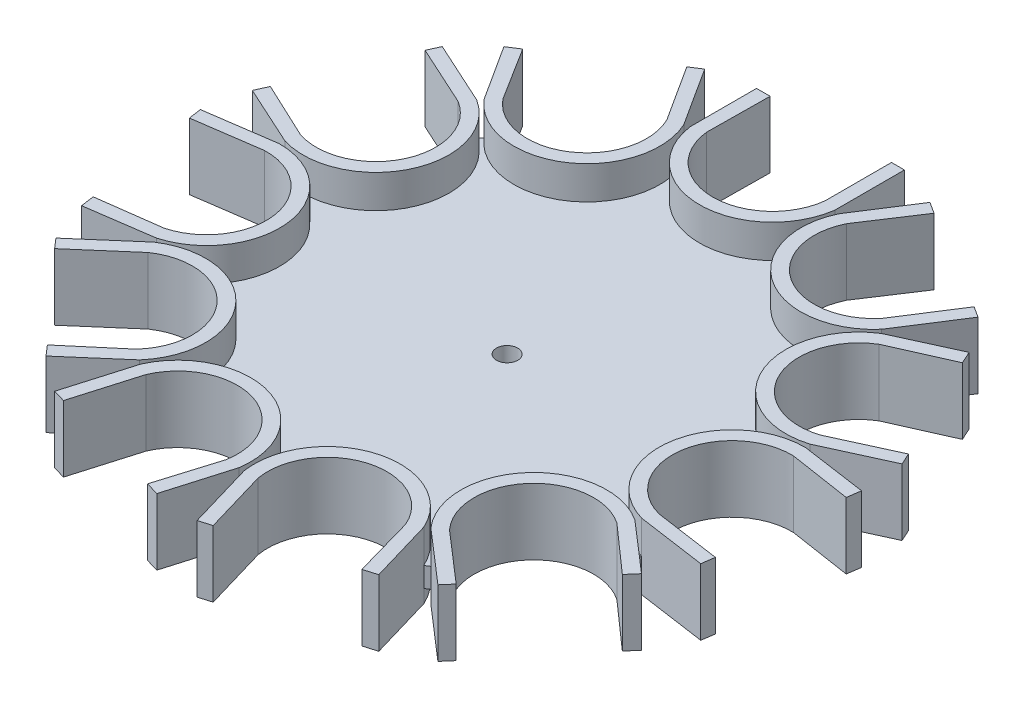
SolidWorks part; units mm, degrees
ref_plane "Front Plane" through (0, 0, 0) normal (0, 0, 1) x (1, 0, 0)
ref_plane "Top Plane" through (0, 0, 0) normal (0, 1, 0) x (1, 0, 0)
ref_plane "Right Plane" through (0, 0, 0) normal (1, 0, 0) x (0, 0, -1)
sketch "Sketch2" plane through (0, 0, 0) normal (0, 1, 0) x (1, 0, 0)
  line L0 (0, 0) -> (0, 40)
  line L1 (-9, 40) -> (-9, 45)
  line L2 (-9, 45) -> (9, 45)
  line L3 (9, 45) -> (9, 40)
  line L4 (14.0544, 38.5159) -> (16.7576, 42.7222)
  line L5 (31.9001, 32.9906) -> (29.1969, 28.7844)
  line L6 (16.7576, 42.7222) -> (31.9001, 32.9906)
  line L7 (32.6465, 24.8033) -> (37.1947, 26.8804)
  line L8 (44.6722, 10.507) -> (40.124, 8.4299)
  line L9 (37.1947, 26.8804) -> (44.6722, 10.507)
  line L10 (40.8737, 3.2158) -> (45.8228, 2.5042)
  line L11 (43.2611, -15.3126) -> (38.312, -14.601)
  line L12 (45.8228, 2.5042) -> (43.2611, -15.3126)
  line L13 (36.1237, -19.3927) -> (39.9025, -22.667)
  line L14 (28.115, -36.2705) -> (24.3362, -32.9962)
  line L15 (39.9025, -22.667) -> (28.115, -36.2705)
  line L16 (19.9047, -35.8441) -> (21.3134, -40.6416)
  line L17 (4.0425, -45.7128) -> (2.6339, -40.9153)
  line L18 (21.3134, -40.6416) -> (4.0425, -45.7128)
  line L19 (-2.6339, -40.9153) -> (-4.0425, -45.7128)
  line L20 (-21.3134, -40.6416) -> (-19.9047, -35.8441)
  line L21 (-4.0425, -45.7128) -> (-21.3134, -40.6416)
  line L22 (-24.3362, -32.9962) -> (-28.115, -36.2705)
  line L23 (-39.9025, -22.667) -> (-36.1237, -19.3927)
  line L24 (-28.115, -36.2705) -> (-39.9025, -22.667)
  line L25 (-38.312, -14.601) -> (-43.2611, -15.3126)
  line L26 (-45.8228, 2.5042) -> (-40.8737, 3.2158)
  line L27 (-43.2611, -15.3126) -> (-45.8228, 2.5042)
  line L28 (-40.124, 8.4299) -> (-44.6722, 10.507)
  line L29 (-37.1947, 26.8804) -> (-32.6465, 24.8033)
  line L30 (-44.6722, 10.507) -> (-37.1947, 26.8804)
  line L31 (-29.1969, 28.7844) -> (-31.9001, 32.9906)
  line L32 (-16.7576, 42.7222) -> (-14.0544, 38.5159)
  line L33 (-31.9001, 32.9906) -> (-16.7576, 42.7222)
  arc A0 (-9, 40) -> (9, 40) centre (0, 40) ccw
  arc A1 (14.0544, 38.5159) -> (29.1969, 28.7844) centre (21.6256, 33.6501) ccw
  arc A2 (32.6465, 24.8033) -> (40.124, 8.4299) centre (36.3853, 16.6166) ccw
  arc A3 (40.8737, 3.2158) -> (38.312, -14.601) centre (39.5929, -5.6926) ccw
  arc A4 (36.1237, -19.3927) -> (24.3362, -32.9962) centre (30.23, -26.1944) ccw
  arc A5 (19.9047, -35.8441) -> (2.6339, -40.9153) centre (11.2693, -38.3797) ccw
  arc A6 (-2.6339, -40.9153) -> (-19.9047, -35.8441) centre (-11.2693, -38.3797) ccw
  arc A7 (-24.3362, -32.9962) -> (-36.1237, -19.3927) centre (-30.23, -26.1944) ccw
  arc A8 (-38.312, -14.601) -> (-40.8737, 3.2158) centre (-39.5929, -5.6926) ccw
  arc A9 (-40.124, 8.4299) -> (-32.6465, 24.8033) centre (-36.3853, 16.6166) ccw
  arc A10 (-29.1969, 28.7844) -> (-14.0544, 38.5159) centre (-21.6256, 33.6501) ccw
  circle A11 centre (0, 0) radius 45.8912
  point P60 (0, 0)
  dimension "D2" = 18
  dimension "D1" = 40
  dimension "D3" = 5
  dimension "D4" = 11
extrude "Boss-Extrude4" add sketch "Sketch2" along normal blind 3
sketch "Sketch4" plane through (0, 3, 0) normal (0, 1, 0) x (1, 0, 0)
  circle A0 centre (0, 0) radius 1.6
  dimension "D1" = 3.2
extrude "Cut-Extrude1" cut sketch "Sketch4" against normal blind 3
fillet "Fillet1" [suppressed] radius 5
sketch "Sketch5" plane through (0, 3, 0) normal (0, 1, 0) x (1, 0, 0)
  arc A0 (-30.6093, 34.1917) -> (-18.3862, 42.0469) centre (-21.6256, 33.6501) ccw
  arc A1 (-7.2648, 45.3125) -> (7.2648, 45.3125) centre (0, 40) ccw
  arc A2 (18.3862, 42.0469) -> (30.6093, 34.1917) centre (21.6256, 33.6501) ccw
  arc A3 (38.1998, 25.4318) -> (44.2356, 12.2152) centre (36.3853, 16.6166) ccw
  arc A4 (45.8852, 0.7422) -> (43.8174, -13.6395) centre (39.5929, -5.6926) ccw
  arc A5 (39.0023, -24.183) -> (29.4875, -35.1637) centre (30.23, -26.1944) ccw
  arc A6 (19.7365, -41.4303) -> (5.7955, -45.5238) centre (11.2693, -38.3797) ccw
  arc A7 (-5.7955, -45.5238) -> (-19.7365, -41.4303) centre (-11.2693, -38.3797) ccw
  arc A8 (-29.4875, -35.1637) -> (-39.0023, -24.183) centre (-30.23, -26.1944) ccw
  arc A9 (-43.8174, -13.6395) -> (-45.8852, 0.7422) centre (-39.5929, -5.6926) ccw
  arc A10 (-44.2356, 12.2152) -> (-38.1998, 25.4318) centre (-36.3853, 16.6166) ccw
  arc A11 (-44.5811, 10.887) -> (-37.4222, 26.5627) centre (-36.3853, 16.6166) ccw
  arc A12 (-31.6181, 33.2611) -> (-17.1207, 42.5779) centre (-21.6256, 33.6501) ccw
  arc A13 (-8.6165, 45.075) -> (8.6165, 45.075) centre (0, 40) ccw
  arc A14 (17.1207, 42.5779) -> (31.6181, 33.2611) centre (21.6256, 33.6501) ccw
  arc A15 (37.4222, 26.5627) -> (44.5811, 10.887) centre (36.3853, 16.6166) ccw
  arc A16 (45.8425, 2.114) -> (43.3899, -14.9437) centre (39.5929, -5.6926) ccw
  arc A17 (39.708, -23.0059) -> (28.4228, -36.0298) centre (30.23, -26.1944) ccw
  arc A18 (20.9666, -40.8216) -> (4.4316, -45.6767) centre (11.2693, -38.3797) ccw
  arc A19 (-4.4316, -45.6767) -> (-20.9666, -40.8216) centre (-11.2693, -38.3797) ccw
  arc A20 (-28.4228, -36.0298) -> (-39.708, -23.0059) centre (-30.23, -26.1944) ccw
  arc A21 (-43.3899, -14.9437) -> (-45.8425, 2.114) centre (-39.5929, -5.6926) ccw
  arc A22 (-44.2356, 12.2152) -> (-44.5811, 10.887) centre (0, 0) ccw
  arc A23 (-30.6093, 34.1917) -> (-31.6181, 33.2611) centre (0, 0) ccw
  arc A24 (-7.2648, 45.3125) -> (-8.6165, 45.075) centre (0, 0) ccw
  arc A25 (18.3862, 42.0469) -> (17.1207, 42.5779) centre (0, 0) ccw
  arc A26 (38.1998, 25.4318) -> (37.4222, 26.5627) centre (0, 0) ccw
  arc A27 (45.8852, 0.7422) -> (45.8425, 2.114) centre (0, 0) ccw
  arc A28 (39.0023, -24.183) -> (39.708, -23.0059) centre (0, 0) ccw
  arc A29 (-20.9666, -40.8216) -> (-19.7365, -41.4303) centre (0, 0) ccw
  arc A30 (-29.4875, -35.1637) -> (-28.4228, -36.0298) centre (0, 0) ccw
  arc A31 (-43.8174, -13.6395) -> (-43.3899, -14.9437) centre (0, 0) ccw
  circle A32 centre (-21.6256, 33.6501) radius 10 construction
  circle A33 centre (-21.6256, 33.6501) radius 9 construction
  circle A34 centre (0, 40) radius 10 construction
  circle A35 centre (0, 40) radius 9 construction
  circle A36 centre (21.6256, 33.6501) radius 10 construction
  circle A37 centre (21.6256, 33.6501) radius 9 construction
  circle A38 centre (36.3853, 16.6166) radius 10 construction
  circle A39 centre (36.3853, 16.6166) radius 9 construction
  circle A40 centre (39.5929, -5.6926) radius 10 construction
  circle A41 centre (39.5929, -5.6926) radius 9 construction
  circle A42 centre (-39.5929, -5.6926) radius 10 construction
  circle A43 centre (-39.5929, -5.6926) radius 9 construction
  circle A44 centre (-36.3853, 16.6166) radius 10 construction
  circle A45 centre (-36.3853, 16.6166) radius 9 construction
  circle A46 centre (-30.23, -26.1944) radius 10 construction
  circle A47 centre (-30.23, -26.1944) radius 9 construction
  arc A48 (-5.7955, -45.5238) -> (-4.4316, -45.6767) centre (0, 0) ccw
  circle A49 centre (-11.2693, -38.3797) radius 10 construction
  circle A50 centre (-11.2693, -38.3797) radius 9 construction
  arc A51 (19.7365, -41.4303) -> (20.9666, -40.8216) centre (0, 0) ccw
  circle A52 centre (11.2693, -38.3797) radius 9 construction
  circle A53 centre (11.2693, -38.3797) radius 10 construction
  circle A54 centre (30.23, -26.1944) radius 10 construction
  circle A55 centre (30.23, -26.1944) radius 9 construction
  arc A56 (-17.1207, 42.5779) -> (-18.3862, 42.0469) centre (0, 0) ccw
  arc A57 (8.6165, 45.075) -> (7.2648, 45.3125) centre (0, 0) ccw
  arc A58 (31.6181, 33.2611) -> (30.6093, 34.1917) centre (0, 0) ccw
  arc A59 (44.5811, 10.887) -> (44.2356, 12.2152) centre (0, 0) ccw
  arc A60 (43.3899, -14.9437) -> (43.8174, -13.6395) centre (0, 0) ccw
  arc A61 (28.4228, -36.0298) -> (29.4875, -35.1637) centre (0, 0) ccw
  arc A62 (4.4316, -45.6767) -> (5.7955, -45.5238) centre (0, 0) ccw
  arc A63 (-39.708, -23.0059) -> (-39.0023, -24.183) centre (0, 0) ccw
  arc A64 (-45.8425, 2.114) -> (-45.8852, 0.7422) centre (0, 0) ccw
  arc A65 (-37.4222, 26.5627) -> (-38.1998, 25.4318) centre (0, 0) ccw
  point P26 (0, 0)
  dimension "D2" = 1
  dimension "D3" = 1
  dimension "D1" = 11
extrude "Boss-Extrude5" [suppressed] add sketch "Sketch5" along normal blind 5
fillet "Fillet2" [suppressed] radius 5
sketch "Sketch8" plane through (0, 3, 0) normal (0, 1, 0) x (1, 0, 0)
  arc A0 (-8.9429, 38.9875) -> (8.9429, 38.9875) centre (0, 40) ccw
  arc A1 (-10.8955, 38.4875) -> (10.8955, 38.4875) centre (0, 40) ccw
  arc A2 (10.8955, 38.4875) -> (8.9429, 38.9875) centre (0, 0) ccw
  arc A3 (-8.9429, 38.9875) -> (-10.8955, 38.4875) centre (0, 0) ccw
  circle A4 centre (0, 40) radius 11 construction
  circle A5 centre (0, 40) radius 9 construction
  arc A6 (11.642, 38.2683) -> (29.9738, 26.4872) centre (21.6256, 33.6501) ccw
  arc A7 (29.9738, 26.4872) -> (28.6015, 27.9635) centre (0, 0) ccw
  arc A8 (13.555, 37.6333) -> (28.6015, 27.9635) centre (21.6256, 33.6501) ccw
  arc A9 (13.555, 37.6333) -> (11.642, 38.2683) centre (0, 0) ccw
  arc A10 (30.4833, 25.8992) -> (39.5356, 6.0774) centre (36.3853, 16.6166) ccw
  arc A11 (39.5356, 6.0774) -> (39.1793, 8.0613) centre (0, 0) ccw
  arc A12 (31.7493, 24.3307) -> (39.1793, 8.0613) centre (36.3853, 16.6166) ccw
  arc A13 (31.7493, 24.3307) -> (30.4833, 25.8992) centre (0, 0) ccw
  arc A14 (39.6463, 5.3073) -> (36.5452, -16.262) centre (39.5929, -5.6926) ccw
  arc A15 (36.5452, -16.262) -> (37.318, -14.4003) centre (0, 0) ccw
  arc A16 (39.8634, 3.3033) -> (37.318, -14.4003) centre (39.5929, -5.6926) ccw
  arc A17 (39.8634, 3.3033) -> (39.6463, 5.3073) centre (0, 0) ccw
  arc A18 (36.222, -16.9697) -> (21.9519, -33.4382) centre (30.23, -26.1944) ccw
  arc A19 (21.9519, -33.4382) -> (23.6085, -32.2899) centre (0, 0) ccw
  arc A20 (35.3211, -18.7728) -> (23.6085, -32.2899) centre (30.23, -26.1944) ccw
  arc A21 (35.3211, -18.7728) -> (36.222, -16.9697) centre (0, 0) ccw
  arc A22 (21.2974, -33.8589) -> (0.389, -39.9981) centre (11.2693, -38.3797) ccw
  arc A23 (0.389, -39.9981) -> (2.4034, -39.9277) centre (0, 0) ccw
  arc A24 (19.5647, -34.8887) -> (2.4034, -39.9277) centre (11.2693, -38.3797) ccw
  arc A25 (19.5647, -34.8887) -> (21.2974, -33.8589) centre (0, 0) ccw
  arc A26 (-0.389, -39.9981) -> (-21.2974, -33.8589) centre (-11.2693, -38.3797) ccw
  arc A27 (-21.2974, -33.8589) -> (-19.5647, -34.8887) centre (0, 0) ccw
  arc A28 (-2.4034, -39.9277) -> (-19.5647, -34.8887) centre (-11.2693, -38.3797) ccw
  arc A29 (-2.4034, -39.9277) -> (-0.389, -39.9981) centre (0, 0) ccw
  arc A30 (-21.9519, -33.4382) -> (-36.222, -16.9697) centre (-30.23, -26.1944) ccw
  arc A31 (-36.222, -16.9697) -> (-35.3211, -18.7728) centre (0, 0) ccw
  arc A32 (-23.6085, -32.2899) -> (-35.3211, -18.7728) centre (-30.23, -26.1944) ccw
  arc A33 (-23.6085, -32.2899) -> (-21.9519, -33.4382) centre (0, 0) ccw
  arc A34 (-36.5452, -16.262) -> (-39.6463, 5.3073) centre (-39.5929, -5.6926) ccw
  arc A35 (-39.6463, 5.3073) -> (-39.8634, 3.3033) centre (0, 0) ccw
  arc A36 (-37.318, -14.4003) -> (-39.8634, 3.3033) centre (-39.5929, -5.6926) ccw
  arc A37 (-37.318, -14.4003) -> (-36.5452, -16.262) centre (0, 0) ccw
  arc A38 (-39.5356, 6.0774) -> (-30.4833, 25.8992) centre (-36.3853, 16.6166) ccw
  arc A39 (-30.4833, 25.8992) -> (-31.7493, 24.3307) centre (0, 0) ccw
  arc A40 (-39.1793, 8.0613) -> (-31.7493, 24.3307) centre (-36.3853, 16.6166) ccw
  arc A41 (-39.1793, 8.0613) -> (-39.5356, 6.0774) centre (0, 0) ccw
  arc A42 (-29.9738, 26.4872) -> (-11.642, 38.2683) centre (-21.6256, 33.6501) ccw
  arc A43 (-11.642, 38.2683) -> (-13.555, 37.6333) centre (0, 0) ccw
  arc A44 (-28.6015, 27.9635) -> (-13.555, 37.6333) centre (-21.6256, 33.6501) ccw
  arc A45 (-28.6015, 27.9635) -> (-29.9738, 26.4872) centre (0, 0) ccw
  point P74 (0, 0)
  dimension "D1" = 2
  dimension "D2" = 11
extrude "Boss-Extrude6" add sketch "Sketch8" along normal blind 5 and the other way blind 5
sketch "Sketch9" plane through (0, 3, 0) normal (0, 1, 0) x (1, 0, 0)
  circle A0 centre (0, 0) radius 40
  circle A1 centre (0, 0) radius 46.8871
extrude "Cut-Extrude2" cut sketch "Sketch9" against normal blind 10
sketch "Sketch10" plane through (0, 8, 0) normal (0, 1, 0) x (1, 0, 0)
  line L0 (-10.8955, 38.4875) -> (-10.8955, 48.4875)
  line L1 (-10.8955, 48.4875) -> (-8.8439, 48.4875)
  line L2 (-8.8439, 48.4875) -> (-8.9429, 38.9875)
  line L3 (-8.9429, 38.9875) -> (-10.8955, 38.4875)
  line L4 (8.9429, 38.9875) -> (8.9429, 48.9875)
  line L5 (8.9429, 48.9875) -> (10.8955, 48.9875)
  line L6 (10.8955, 48.9875) -> (10.8955, 38.4875)
  line L7 (10.8955, 38.4875) -> (8.9429, 38.9875)
  line L8 (18.7743, 45.5717) -> (13.555, 37.6333)
  line L9 (11.642, 38.2683) -> (17.0484, 46.6808)
  line L10 (17.0484, 46.6808) -> (18.7743, 45.5717)
  line L11 (13.555, 37.6333) -> (11.642, 38.2683)
  line L12 (29.9738, 26.4872) -> (28.6015, 27.9635)
  line L13 (28.6015, 27.9635) -> (34.0079, 36.376)
  line L14 (34.0079, 36.376) -> (35.6505, 35.3203)
  line L15 (35.6505, 35.3203) -> (29.9738, 26.4872)
  line L16 (40.4319, 28.1872) -> (31.7493, 24.3307)
  line L17 (30.4833, 25.8992) -> (39.5796, 30.0533)
  line L18 (39.5796, 30.0533) -> (40.4319, 28.1872)
  line L19 (31.7493, 24.3307) -> (30.4833, 25.8992)
  line L20 (39.5356, 6.0774) -> (39.1793, 8.0613)
  line L21 (39.1793, 8.0613) -> (48.2756, 12.2154)
  line L22 (48.2756, 12.2154) -> (49.0868, 10.4392)
  line L23 (49.0868, 10.4392) -> (39.5356, 6.0774)
  line L24 (49.2526, 1.8534) -> (39.8634, 3.3033)
  line L25 (39.6463, 5.3073) -> (49.5446, 3.8841)
  line L26 (49.5446, 3.8841) -> (49.2526, 1.8534)
  line L27 (39.8634, 3.3033) -> (39.6463, 5.3073)
  line L28 (36.5452, -16.262) -> (37.318, -14.4003)
  line L29 (37.318, -14.4003) -> (47.2162, -15.8235)
  line L30 (47.2162, -15.8235) -> (46.9383, -17.7563)
  line L31 (46.9383, -17.7563) -> (36.5452, -16.262)
  line L32 (42.4359, -25.0688) -> (35.3211, -18.7728)
  line L33 (36.222, -16.9697) -> (43.7795, -23.5183)
  line L34 (43.7795, -23.5183) -> (42.4359, -25.0688)
  line L35 (35.3211, -18.7728) -> (36.222, -16.9697)
  line L36 (21.9519, -33.4382) -> (23.6085, -32.2899)
  line L37 (23.6085, -32.2899) -> (31.166, -38.8386)
  line L38 (31.166, -38.8386) -> (29.8872, -40.3143)
  line L39 (29.8872, -40.3143) -> (21.9519, -33.4382)
  line L40 (22.1462, -44.0318) -> (19.5647, -34.8887)
  line L41 (21.2974, -33.8589) -> (24.1147, -43.4538)
  line L42 (24.1147, -43.4538) -> (22.1462, -44.0318)
  line L43 (19.5647, -34.8887) -> (21.2974, -33.8589)
  line L44 (0.389, -39.9981) -> (2.4034, -39.9277)
  line L45 (2.4034, -39.9277) -> (5.2208, -49.5227)
  line L46 (5.2208, -49.5227) -> (3.3472, -50.0728)
  line L47 (3.3472, -50.0728) -> (0.389, -39.9981)
  line L48 (-5.1748, -49.015) -> (-2.4034, -39.9277)
  line L49 (-0.389, -39.9981) -> (-3.2063, -49.593)
  line L50 (-3.2063, -49.593) -> (-5.1748, -49.015)
  line L51 (-2.4034, -39.9277) -> (-0.389, -39.9981)
  line L52 (-21.2974, -33.8589) -> (-19.5647, -34.8887)
  line L53 (-19.5647, -34.8887) -> (-22.382, -44.4837)
  line L54 (-22.382, -44.4837) -> (-24.2555, -43.9335)
  line L55 (-24.2555, -43.9335) -> (-21.2974, -33.8589)
  line L56 (-30.8529, -38.4364) -> (-23.6085, -32.2899)
  line L57 (-21.9519, -33.4382) -> (-29.5094, -39.9868)
  line L58 (-29.5094, -39.9868) -> (-30.8529, -38.4364)
  line L59 (-23.6085, -32.2899) -> (-21.9519, -33.4382)
  line L60 (-36.222, -16.9697) -> (-35.3211, -18.7728)
  line L61 (-35.3211, -18.7728) -> (-42.8786, -25.3214)
  line L62 (-42.8786, -25.3214) -> (-44.1573, -23.8457)
  line L63 (-44.1573, -23.8457) -> (-36.222, -16.9697)
  line L64 (-46.7353, -15.6544) -> (-37.318, -14.4003)
  line L65 (-36.5452, -16.262) -> (-46.4434, -17.6851)
  line L66 (-46.4434, -17.6851) -> (-46.7353, -15.6544)
  line L67 (-37.318, -14.4003) -> (-36.5452, -16.262)
  line L68 (-39.6463, 5.3073) -> (-39.8634, 3.3033)
  line L69 (-39.8634, 3.3033) -> (-49.7616, 1.8802)
  line L70 (-49.7616, 1.8802) -> (-50.0395, 3.813)
  line L71 (-50.0395, 3.813) -> (-39.6463, 5.3073)
  line L72 (-47.7797, 12.0977) -> (-39.1793, 8.0613)
  line L73 (-39.5356, 6.0774) -> (-48.6319, 10.2315)
  line L74 (-48.6319, 10.2315) -> (-47.7797, 12.0977)
  line L75 (-39.1793, 8.0613) -> (-39.5356, 6.0774)
  line L76 (-30.4833, 25.8992) -> (-31.7493, 24.3307)
  line L77 (-31.7493, 24.3307) -> (-40.8456, 28.4849)
  line L78 (-40.8456, 28.4849) -> (-40.0344, 30.2611)
  line L79 (-40.0344, 30.2611) -> (-30.4833, 25.8992)
  line L80 (-33.6543, 36.0089) -> (-28.6015, 27.9635)
  line L81 (-29.9738, 26.4872) -> (-35.3802, 34.8997)
  line L82 (-35.3802, 34.8997) -> (-33.6543, 36.0089)
  line L83 (-28.6015, 27.9635) -> (-29.9738, 26.4872)
  line L84 (-11.642, 38.2683) -> (-13.555, 37.6333)
  line L85 (-13.555, 37.6333) -> (-18.9614, 46.0458)
  line L86 (-18.9614, 46.0458) -> (-17.3187, 47.1015)
  line L87 (-17.3187, 47.1015) -> (-11.642, 38.2683)
  point P95 (0, 0)
  dimension "D1" = 10
  dimension "D2" = 10
  dimension "D3" = 2.0516
  dimension "D4" = 11
extrude "Boss-Extrude7" add sketch "Sketch10" against normal up to surface (10 mm away)
